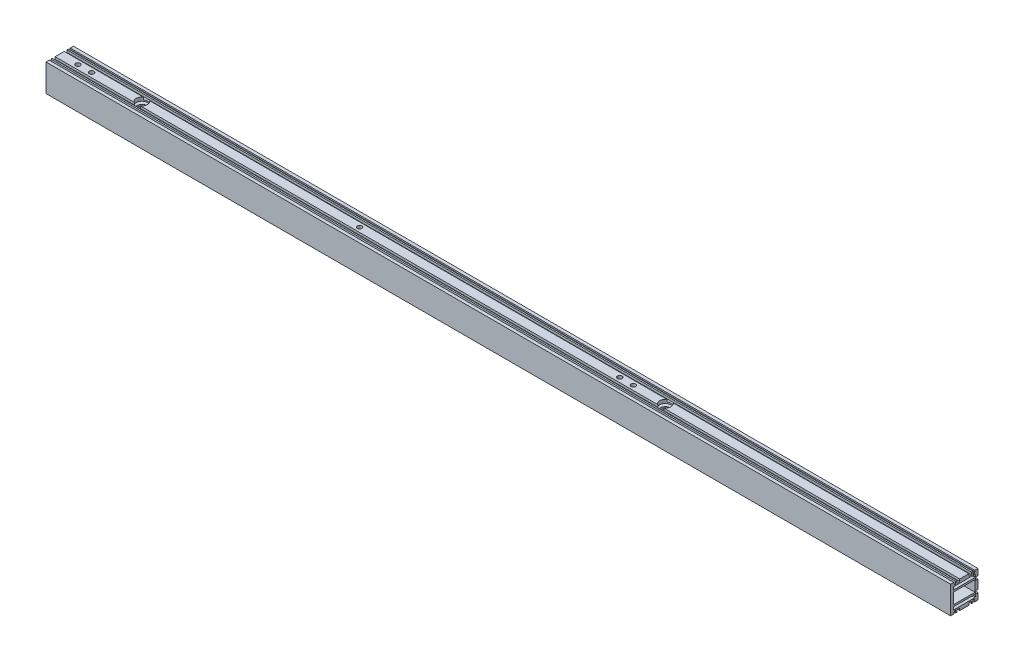
SolidWorks part; units mm, degrees
ref_plane "前视基准面" through (0, 0, 0) normal (0, 0, 1) x (1, 0, 0)
ref_plane "上视基准面" through (0, 0, 0) normal (0, 1, 0) x (1, 0, 0)
ref_plane "右视基准面" through (0, 0, 0) normal (1, 0, 0) x (0, 0, -1)
sketch "草图1" plane through (0, 0, 0) normal (1, 0, 0) x (0, 0, -1)
  line L0 (-15, 15) -> (15, -15) construction
  line L1 (-15, 15) -> (-11.5, 15)
  line L2 (-15, 15) -> (-15, -15)
  line L3 (-15, -15) -> (-11.5, -15)
  line L4 (15, 15) -> (15, 8)
  line L5 (15, 15) -> (-15, -15) construction
  line L6 (-11.5, 15) -> (-11.5, 13.5)
  line L7 (-11.5, 13.5) -> (-11, 13.5)
  line L8 (-11, 13.5) -> (-11, 12)
  line L9 (-11, 12) -> (-9.5, 12)
  line L10 (-9.5, 12) -> (-9.5, 15)
  line L11 (-9.5, 15) -> (-8, 15)
  line L12 (-8, 15) -> (-8, 12.5)
  line L13 (-8, 12.5) -> (-5, 12.5)
  line L14 (-5, 12.5) -> (-5, 15)
  line L15 (-5, 15) -> (5, 15)
  line L16 (0, 21.5201) -> (0, -18.309) construction
  line L17 (0, 55) -> (0, -55) construction
  line L18 (5, 12.5) -> (5, 15)
  line L19 (8, 12.5) -> (5, 12.5)
  line L20 (8, 15) -> (8, 12.5)
  line L21 (9.5, 15) -> (8, 15)
  line L22 (9.5, 12) -> (9.5, 15)
  line L23 (11, 12) -> (9.5, 12)
  line L24 (11, 13.5) -> (11, 12)
  line L25 (11.5, 13.5) -> (11, 13.5)
  line L26 (11.5, 15) -> (11.5, 13.5)
  line L27 (8, 15) -> (9.5, 15)
  line L28 (11.5, 15) -> (15, 15)
  line L29 (-19.8303, 0) -> (22.13, 0) construction
  line L30 (55, 0) -> (-55, 0) construction
  line L31 (8, -15) -> (9.5, -15)
  line L32 (11.5, -15) -> (11.5, -13.5)
  line L33 (11.5, -13.5) -> (11, -13.5)
  line L34 (11, -13.5) -> (11, -12)
  line L35 (11, -12) -> (9.5, -12)
  line L36 (9.5, -12) -> (9.5, -15)
  line L37 (9.5, -15) -> (8, -15)
  line L38 (8, -15) -> (8, -12.5)
  line L39 (8, -12.5) -> (5, -12.5)
  line L40 (5, -12.5) -> (5, -15)
  line L41 (-5, -15) -> (5, -15)
  line L42 (-5, -12.5) -> (-5, -15)
  line L43 (-8, -12.5) -> (-5, -12.5)
  line L44 (-8, -15) -> (-8, -12.5)
  line L45 (-9.5, -15) -> (-8, -15)
  line L46 (-9.5, -12) -> (-9.5, -15)
  line L47 (-11, -12) -> (-9.5, -12)
  line L48 (-11, -13.5) -> (-11, -12)
  line L49 (-11.5, -13.5) -> (-11, -13.5)
  line L50 (-11.5, -15) -> (-11.5, -13.5)
  line L51 (-9.5, -15) -> (-8, -15)
  line L52 (-5, -15) -> (5, -15)
  line L53 (8, -15) -> (9.5, -15)
  line L54 (11.5, -15) -> (15, -15)
  line L55 (15, 8) -> (12.5, 8)
  line L56 (12.5, 8) -> (12.5, 5)
  line L57 (12.5, 5) -> (15, 5)
  line L58 (12.5, -5) -> (15, -5)
  line L59 (12.5, -8) -> (12.5, -5)
  line L60 (15, -8) -> (12.5, -8)
  line L61 (15, 5) -> (15, -5)
  line L62 (15, -8) -> (15, -15)
  line L63 (12, -10.5) -> (12, -8.5)
  line L64 (-11.5, 11) -> (11.5, 11)
  line L65 (-12, 10.5) -> (-12, 8.5)
  line L66 (-11.5, 8) -> (11.5, 8)
  line L67 (12, 10.5) -> (12, 8.5)
  line L68 (-11.5, -8) -> (11.5, -8)
  line L69 (-12, -10.5) -> (-12, -8.5)
  line L70 (-11.5, -11) -> (11.5, -11)
  line L72 (-11.75, 6) -> (11.75, 6)
  line L73 (-11.75, 6) -> (-11.75, -6)
  line L74 (-11.75, -6) -> (11.75, -6)
  line L75 (11.75, 6) -> (11.75, -6)
  arc A0 (12, 8.5) -> (11.5, 8) centre (11.5, 8.5) cw
  arc A1 (11.5, 11) -> (12, 10.5) centre (11.5, 10.5) cw
  arc A2 (-11.5, 11) -> (-12, 10.5) centre (-11.5, 10.5) ccw
  arc A3 (-11.5, 8) -> (-12, 8.5) centre (-11.5, 8.5) cw
  arc A8 (-11.5, -8) -> (-12, -8.5) centre (-11.5, -8.5) ccw
  arc A9 (-11.5, -11) -> (-12, -10.5) centre (-11.5, -10.5) cw
  arc A10 (11.5, -11) -> (12, -10.5) centre (11.5, -10.5) ccw
  arc A11 (12, -8.5) -> (11.5, -8) centre (11.5, -8.5) ccw
  point P69 (12, 11)
  point P72 (-12, 11)
  point P77 (-11, -13.5)
  point P80 (11, -13.5)
  point P83 (11, 13.5)
  point P86 (-11, 13.5)
  point P99 (-12, -11)
  point P100 (12, -11)
  dimension "D17" = 0.5
  dimension "D1" = 3.5
  dimension "D2" = 1.5
  dimension "D3" = 0.5
  dimension "D4" = 1.5
  dimension "D5" = 3
  dimension "D6" = 30
  dimension "D7" = 30
  dimension "D8" = 1.5
  dimension "D9" = 2.5
  dimension "D10" = 3
  dimension "D11" = 2.5
  dimension "D12" = 7
  dimension "D13" = 3
  dimension "D14" = 4
  dimension "D15" = 3
  dimension "D16" = 24
  dimension "D19" = 23.5
  dimension "D20" = 12
extrude "凸台-拉伸1" add sketch "草图1" along normal mid plane 991
hole_wizard "M6 螺纹孔1" positions "草图3" profile "草图2" tap size "M6" standard "GB"
sketch "草图3" plane through (0, -15, 0) normal (0, -1, 0) x (-1, 0, 0)
  point P0 (-445.5, 0)
  point P3 (-430.5, 0)
  point P6 (230.5, 0)
  point P9 (245.5, 0)
  point P12 (460.5, 0)
  point P15 (475.5, 0)
sketch "草图2" plane through (445.5, -15, 0) normal (1, 0, 0) x (0, 0, -1)
  line L0 (0, 0) -> (0, 20.5022)
  line L1 (0, 20.5022) -> (2.5, 19)
  line L2 (2.5, 19) -> (2.5, 0)
  line L5 (2.5, 0) -> (0, 0)
  line L10 (0, 20.5022) -> (-2.5, 19) construction
  line L11 (0, -6.35) -> (0, 107.95) construction
  dimension "螺纹孔钻头直径" = 5
  dimension "螺纹孔钻头深度" = 19
  dimension "导头角度" = 118
cosmetic thread "孔螺蚊线1" parameters "D1"=9, "D2"=6
cosmetic thread "孔螺蚊线2" parameters "D1"=9, "D2"=6
cosmetic thread "孔螺蚊线3" parameters "D1"=9, "D2"=6
cosmetic thread "孔螺蚊线4" parameters "D1"=9, "D2"=6
cosmetic thread "孔螺蚊线5" parameters "D1"=9, "D2"=6
cosmetic thread "孔螺蚊线6" parameters "D1"=9, "D2"=6
hole_wizard "M6 螺纹孔2" positions "草图5" profile "草图4" tap size "M6" standard "GB"
sketch "草图5" plane through (0, 0, -15) normal (0, 0, -1) x (-1, 0, 0)
  line L0 (-495.5, -15) -> (495.5, -15) construction
  line L1 (-495.5, 5) -> (-495.5, -5) construction
  line L2 (-495.5, 8) -> (-495.5, 5) construction
  point P0 (-445.5, 0)
  point P3 (-430.5, 0)
  point P7 (-370.5, 0)
  point P9 (-266.5, 0)
  point P18 (-394.5, 0)
  dimension "D1" = 15
  dimension "D2" = 15
  dimension "D3" = 104
  dimension "D4" = 125
  dimension "D5" = 101
  dimension "D10" = 15
sketch "草图4" plane through (445.5, 0, -15) normal (1, 0, 0) x (0, 1, 0)
  line L0 (0, 0) -> (0, 20.5022)
  line L1 (0, 20.5022) -> (2.5, 19)
  line L2 (2.5, 19) -> (2.5, 0)
  line L5 (2.5, 0) -> (0, 0)
  line L10 (0, 20.5022) -> (-2.5, 19) construction
  line L11 (0, -6.35) -> (0, 107.95) construction
  dimension "螺纹孔钻头直径" = 5
  dimension "螺纹孔钻头深度" = 19
  dimension "导头角度" = 118
cosmetic thread "孔螺蚊线7" parameters "D1"=3.25, "D2"=6
cosmetic thread "孔螺蚊线8" parameters "D1"=3.25, "D2"=6
cosmetic thread "孔螺蚊线13" parameters "D1"=3.25, "D2"=6
cosmetic thread "孔螺蚊线14" parameters "D1"=3.25, "D2"=6
cosmetic thread "孔螺蚊线17" parameters "D1"=3.25, "D2"=6
hole_wizard "M6 螺纹孔3" positions "草图7" profile "草图6" tap size "M6" standard "GB"
sketch "草图7" plane through (0, 15, 0) normal (0, 1, 0) x (1, 0, 0)
  line L0 (495.5, -15) -> (-495.5, -15) construction
  line L1 (495.5, -5) -> (495.5, 5) construction
  point P0 (133, 0)
  point P3 (118, 0)
  point P6 (-460.5, 0)
  point P9 (-475.5, 0)
  point P12 (-167, 0)
  dimension "D1" = 15
  dimension "D2" = 662.5
sketch "草图6" plane through (133, 15, 0) normal (1, 0, 0) x (0, 0, 1)
  line L0 (0, 0) -> (0, 20.5022)
  line L1 (0, 20.5022) -> (2.5, 19)
  line L2 (2.5, 19) -> (2.5, 0)
  line L5 (2.5, 0) -> (0, 0)
  line L10 (0, 20.5022) -> (-2.5, 19) construction
  line L11 (0, -6.35) -> (0, 107.95) construction
  dimension "螺纹孔钻头直径" = 5
  dimension "螺纹孔钻头深度" = 19
  dimension "导头角度" = 118
cosmetic thread "孔螺蚊线9" parameters "D1"=9, "D2"=6
cosmetic thread "孔螺蚊线10" parameters "D1"=9, "D2"=6
cosmetic thread "孔螺蚊线11" parameters "D1"=9, "D2"=6
cosmetic thread "孔螺蚊线12" parameters "D1"=9, "D2"=6
cosmetic thread "孔螺蚊线22" parameters "D1"=9, "D2"=6
hole_wizard "Ø12.0 (12) 直径孔1" positions "草图9" profile "草图8" hole size "Ø12.0" standard "GB" end condition through all
sketch "草图9" plane through (0, -15, 0) normal (0, -1, 0) x (-1, 0, 0)
  line L0 (-495.5, 15) -> (495.5, 15) construction
  line L1 (495.5, 11.5) -> (495.5, 15) construction
  line L2 (-495.5, -5) -> (-495.5, 5) construction
  point P0 (-168, 0)
  point P2 (405.5, 0)
  dimension "D1" = 15
  dimension "D2" = 90
  dimension "D3" = 15
  dimension "D4" = 327.5
sketch "草图8" plane through (168, -15, 0) normal (1, 0, 0) x (0, 0, -1)
  line L0 (0, 0) -> (0, 30)
  line L1 (0, 30) -> (6, 30)
  line L2 (6, 30) -> (6, 0)
  line L5 (6, 0) -> (0, 0)
  line L11 (0, -6.35) -> (0, 107.95) construction
  dimension "通孔孔直径" = 12
  dimension "通孔孔深度" = 30
hole_wizard "M4 螺纹孔1" positions "草图11" profile "草图10" tap size "M4" standard "GB"
sketch "草图11" plane through (0, 0, -15) normal (0, 0, -1) x (-1, 0, 0)
  line L0 (-495.5, -15) -> (-171.3166, -15) construction
  line L1 (-495.5, 5) -> (-495.5, -5) construction
  point P0 (-341, 0)
  point P2 (-296, 0)
  point P4 (-236, 0)
  point P6 (-191, 0)
  dimension "D1" = 15
  dimension "D2" = 15
  dimension "D3" = 15
  dimension "D4" = 15
  dimension "D5" = 154.5
  dimension "D6" = 199.5
  dimension "D7" = 259.5
  dimension "D8" = 304.5
sketch "草图10" plane through (341, 0, -15) normal (1, 0, 0) x (0, 1, 0)
  line L0 (0, 0) -> (0, 12.4914)
  line L1 (0, 12.4914) -> (1.65, 11.5)
  line L2 (1.65, 11.5) -> (1.65, 0)
  line L5 (1.65, 0) -> (0, 0)
  line L10 (0, 12.4914) -> (-1.65, 11.5) construction
  line L11 (0, -6.35) -> (0, 107.95) construction
  dimension "螺纹孔钻头直径" = 3.3
  dimension "螺纹孔钻头深度" = 11.5
  dimension "导头角度" = 118
cosmetic thread "孔螺蚊线18" parameters "D1"=3.25, "D2"=4
cosmetic thread "孔螺蚊线19" parameters "D1"=3.25, "D2"=4
cosmetic thread "孔螺蚊线20" parameters "D1"=3.25, "D2"=4
cosmetic thread "孔螺蚊线21" parameters "D1"=3.25, "D2"=4
